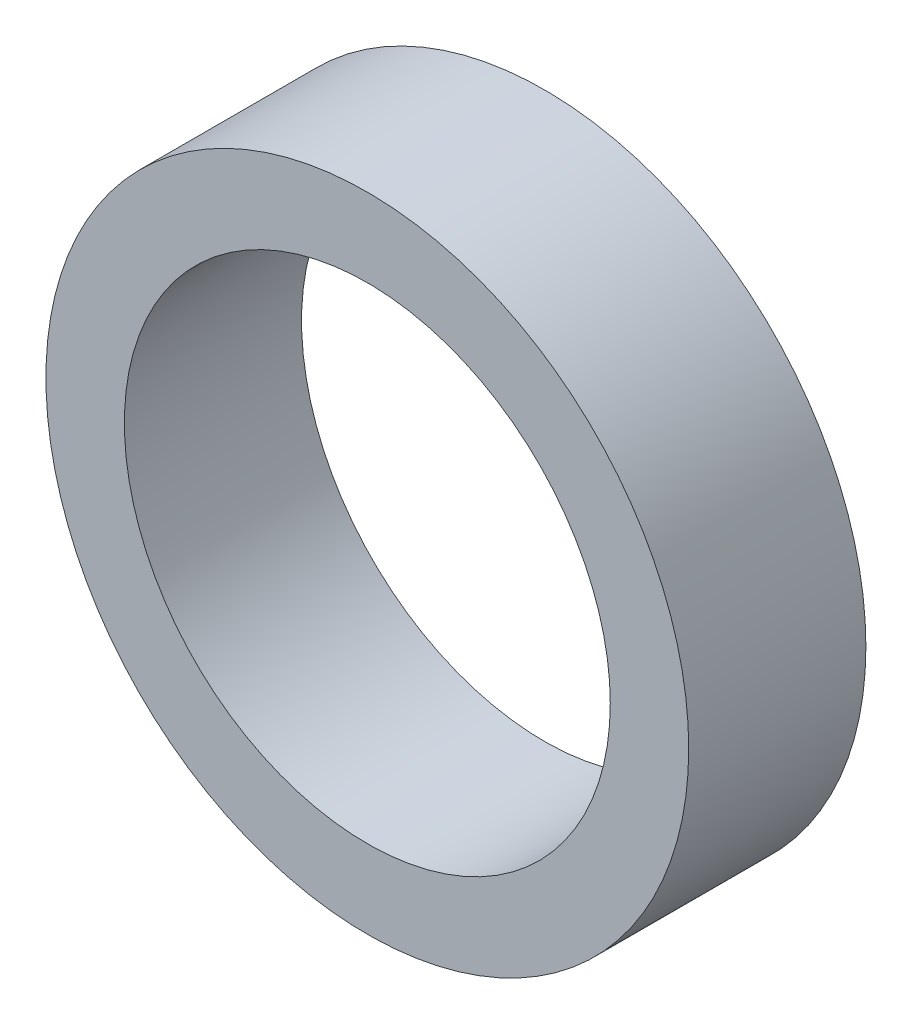
SolidWorks part; units mm, degrees
ref_plane "Спереди" through (0, 0, 0) normal (0, 0, 1) x (1, 0, 0)
ref_plane "Сверху" through (0, 0, 0) normal (0, 1, 0) x (1, 0, 0)
ref_plane "Справа" through (0, 0, 0) normal (1, 0, 0) x (0, 0, -1)
sketch "Эскиз1" plane through (0, 0, 0) normal (0, 0, 1) x (1, 0, 0)
  circle A0 centre (0, 0) radius 127
  circle A1 centre (0, 0) radius 96
extrude "Tire_reference" add sketch "Эскиз1" along normal blind 70 from offset 35
